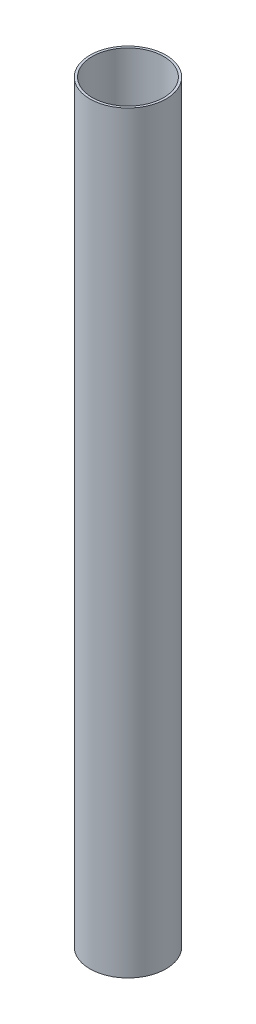
SolidWorks part; units mm, degrees
ref_plane "Front Plane" through (0, 0, 0) normal (0, 0, 1) x (1, 0, 0)
ref_plane "Top Plane" through (0, 0, 0) normal (0, 1, 0) x (1, 0, 0)
ref_plane "Right Plane" through (0, 0, 0) normal (1, 0, 0) x (0, 0, -1)
sketch "Sketch1" plane through (0, 0, 0) normal (0, 1, 0) x (1, 0, 0)
  circle A0 centre (0, 0) radius 57.5
  circle A1 centre (0, 0) radius 54
extrude "Boss-Extrude1" add sketch "Sketch1" along normal blind 1140
